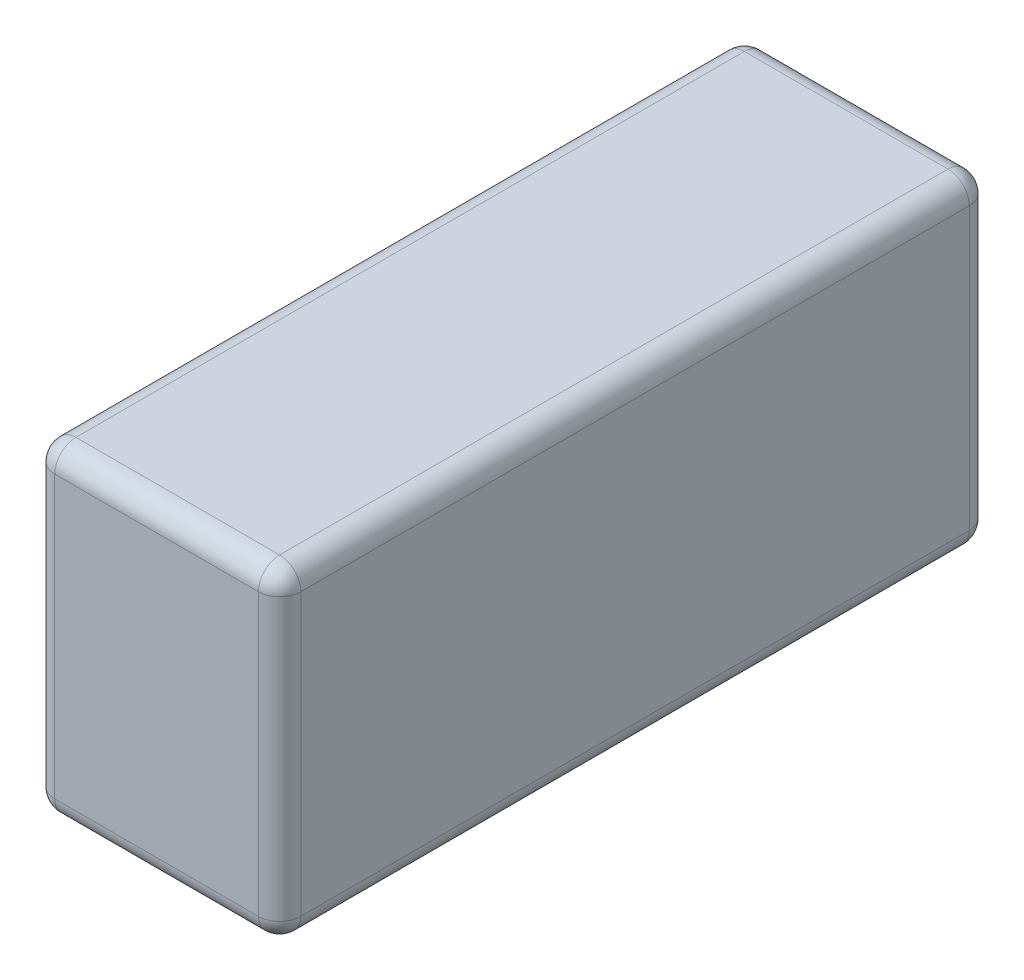
SolidWorks part; units mm, degrees
ref_plane "Спереди" through (0, 0, 0) normal (0, 0, 1) x (1, 0, 0)
ref_plane "Сверху" through (0, 0, 0) normal (0, 1, 0) x (1, 0, 0)
ref_plane "Справа" through (0, 0, 0) normal (1, 0, 0) x (0, 0, -1)
sketch "Эскиз1" plane through (0, 0, 0) normal (0, 1, 0) x (1, 0, 0)
  line L1 (-11.6, 33.5) -> (11.6, 33.5)
  line L2 (-11.6, 33.5) -> (-11.6, -33.5)
  line L3 (-11.6, -33.5) -> (11.6, -33.5)
  line L4 (11.6, 33.5) -> (11.6, -33.5)
  line L5 (-11.6, 33.5) -> (11.6, -33.5) construction
  line L6 (-11.6, -33.5) -> (11.6, 33.5) construction
  point P0 (0, 0)
  dimension "D1" = 23.2
  dimension "D2" = 67
extrude "Бобышка-Вытянуть1" add sketch "Эскиз1" along normal blind 30.5
fillet "Скругление2" radius 2 12 edges at (0, 0, -33.5) (0, 30.5, -33.5) (-11.6, 0, 0) (-11.6, 15.25, -33.5) (-11.6, 30.5, 0) (11.6, 0, 0) (11.6, 30.5, 0) (11.6, 15.25, -33.5) (0, 0, 33.5) (-11.6, 15.25, 33.5) (0, 30.5, 33.5) (11.6, 15.25, 33.5)
